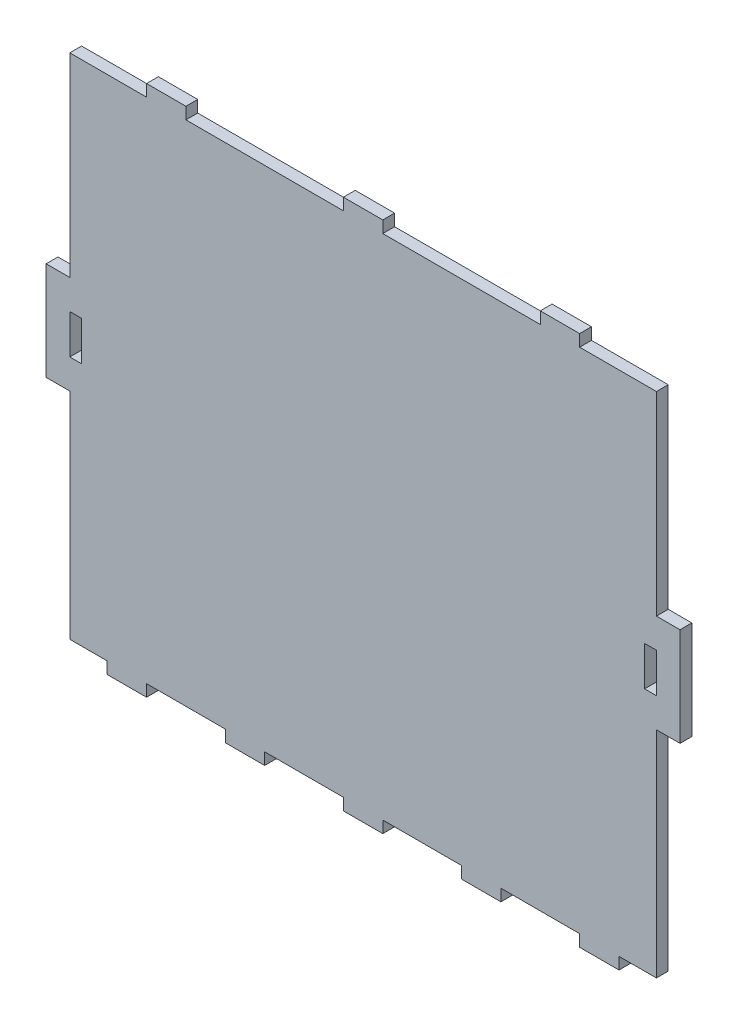
SolidWorks part; units mm, degrees
ref_plane "Front Plane" through (0, 0, 0) normal (0, 0, 1) x (1, 0, 0)
ref_plane "Top Plane" through (0, 0, 0) normal (0, 1, 0) x (1, 0, 0)
ref_plane "Right Plane" through (0, 0, 0) normal (1, 0, 0) x (0, 0, -1)
sketch "Sketch1" plane through (0, 0, 0) normal (0, 0, 1) x (1, 0, 0)
  line L0 (-74.5, 61.9) -> (-55, 61.9)
  line L1 (-55, 61.9) -> (-55, 64.9)
  line L2 (-55, 64.9) -> (-45, 64.9)
  line L3 (-45, 64.9) -> (-45, 61.9)
  line L4 (-45, 61.9) -> (-5, 61.9)
  line L5 (-5, 61.9) -> (-5, 64.9)
  line L6 (-5, 64.9) -> (5, 64.9)
  line L7 (5, 64.9) -> (5, 61.9)
  line L8 (5, 61.9) -> (45, 61.9)
  line L9 (45, 61.9) -> (45, 64.9)
  line L10 (45, 64.9) -> (55, 64.9)
  line L11 (55, 64.9) -> (55, 61.9)
  line L12 (55, 61.9) -> (74.5, 61.9)
  line L13 (74.5, 61.9) -> (74.5, 12.5)
  line L14 (74.5, 12.5) -> (80.5, 12.5)
  line L15 (80.5, 12.5) -> (80.5, -12.5)
  line L16 (80.5, -12.5) -> (74.5, -12.5)
  line L17 (74.5, -12.5) -> (74.5, -67.1)
  line L18 (74.5, -67.1) -> (65, -67.1)
  line L19 (65, -67.1) -> (65, -70.1)
  line L20 (65, -70.1) -> (55, -70.1)
  line L21 (55, -70.1) -> (55, -67.1)
  line L22 (55, -67.1) -> (35, -67.1)
  line L23 (35, -70.1) -> (25, -70.1)
  line L24 (25, -70.1) -> (25, -67.1)
  line L25 (25, -67.1) -> (5, -67.1)
  line L26 (5, -67.1) -> (5, -70.1)
  line L27 (5, -70.1) -> (-5, -70.1)
  line L28 (-5, -70.1) -> (-5, -67.1)
  line L29 (-5, -67.1) -> (-25, -67.1)
  line L30 (-25, -67.1) -> (-25, -70.1)
  line L31 (-25, -70.1) -> (-35, -70.1)
  line L32 (-35, -70.1) -> (-35, -67.1)
  line L33 (35, -70.1) -> (35, -67.1)
  line L34 (-35, -67.1) -> (-55, -67.1)
  line L35 (-55, -67.1) -> (-55, -70.1)
  line L36 (-55, -70.1) -> (-65, -70.1)
  line L37 (-65, -70.1) -> (-65, -67.1)
  line L38 (-65, -67.1) -> (-74.5, -67.1)
  line L39 (-74.5, -67.1) -> (-74.5, -12.5)
  line L40 (-74.5, -12.5) -> (-80.5, -12.5)
  line L41 (-80.5, -12.5) -> (-80.5, 12.5)
  line L42 (-80.5, 12.5) -> (-74.5, 12.5)
  line L43 (-74.5, 12.5) -> (-74.5, 61.9)
  line L44 (55, 0) -> (-55, 0) construction
  line L45 (71.5, 5) -> (71.5, -5)
  line L46 (0, -55) -> (0, 55) construction
  line L47 (74.5, -5) -> (71.5, -5)
  line L48 (-74.5, 5) -> (-71.5, 5)
  line L49 (-74.5, 5) -> (-74.5, -5)
  line L50 (-74.5, -5) -> (-71.5, -5)
  line L51 (-71.5, 5) -> (-71.5, -5)
  line L52 (74.5, 5) -> (74.5, -5)
  line L53 (74.5, 5) -> (71.5, 5)
  point P12 (-71.5, 0)
  point P45 (-74.5, 0)
  point P46 (-80.5, 0)
  point P48 (0, -70.1)
  point P52 (0, 64.9)
  point P53 (-50, 64.9)
  dimension "D1" = 10
  dimension "D2" = 20
  dimension "D3" = 9.5
  dimension "D4" = 6
  dimension "D5" = 40
  dimension "D6" = 10
  dimension "D8" = 149
  dimension "D9" = 129
  dimension "D10" = 25
  dimension "D11" = 3
  dimension "D12" = 3
  dimension "D13" = 10
  dimension "D14" = 3
  dimension "49.4" = 52.4
extrude "Boss-Extrude1" add sketch "Sketch1" along normal blind 3
